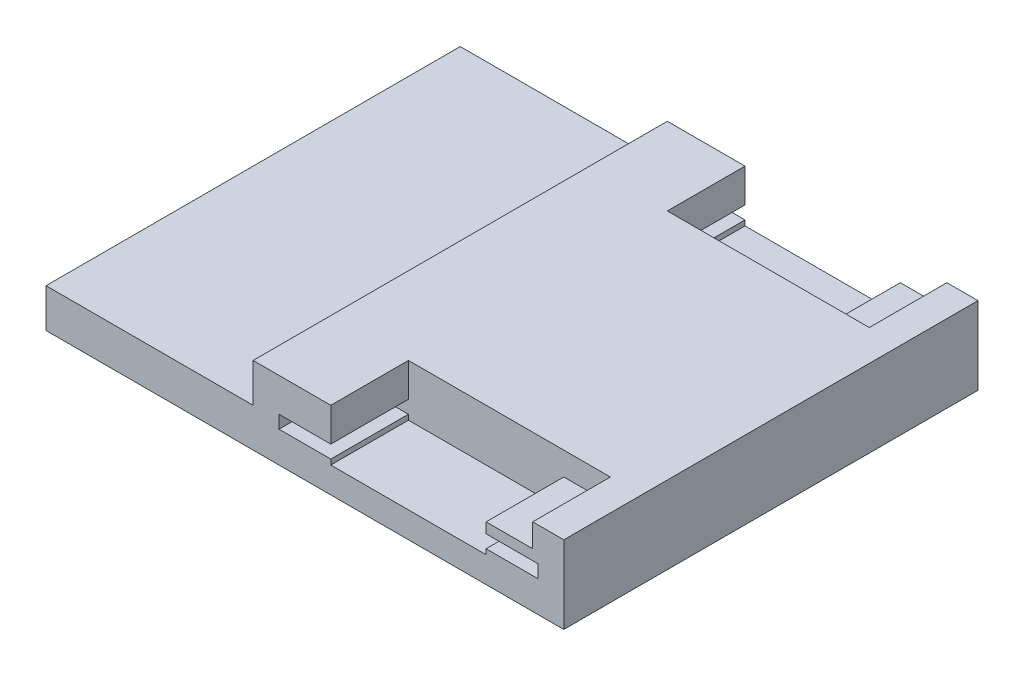
SolidWorks part; units mm, degrees
ref_plane "Front Plane" through (0, 0, 0) normal (0, 0, 1) x (1, 0, 0)
ref_plane "Top Plane" through (0, 0, 0) normal (0, 1, 0) x (1, 0, 0)
ref_plane "Right Plane" through (0, 0, 0) normal (1, 0, 0) x (0, 0, -1)
sketch "Sketch1" plane through (0, 0, 0) normal (0, 1, 0) x (1, 0, 0)
  line L1 (-160, 80) -> (160, 80)
  line L2 (-160, 80) -> (-160, -80)
  line L3 (-160, -80) -> (160, -80)
  line L4 (160, 80) -> (160, -80)
  line L5 (-160, 80) -> (160, -80) construction
  line L6 (-160, -80) -> (160, 80) construction
  point P0 (0, 0)
  dimension "D1" = 320
  dimension "D2" = 160
extrude "Boss-Extrude1" add sketch "Sketch1" along normal blind 20
sketch "Sketch2" plane through (0, 20, 0) normal (0, 1, 0) x (1, 0, 0)
  line L0 (-160, -80) -> (160, -80) construction
  line L1 (-130, -80) -> (-70, -80)
  line L2 (-130, -80) -> (-130, -50)
  line L3 (-130, -50) -> (-70, -50)
  line L4 (-70, -80) -> (-70, -50)
  line L5 (-160, 80) -> (-160, -80) construction
  dimension "D1" = 60
  dimension "D2" = 30
  dimension "D3" = 30
extrude "Cut-Extrude1" cut sketch "Sketch2" against normal blind 28
sketch "Sketch3" plane through (0, 0, 80) normal (0, 0, 1) x (1, 0, 0)
  line L0 (-130, 0) -> (-130, 20) construction
  line L1 (-130, 7) -> (-150, 7)
  line L2 (-130, 7) -> (-130, 2)
  line L3 (-130, 2) -> (-150, 2)
  line L4 (-150, 7) -> (-150, 2)
  line L5 (-160, 0) -> (-130, 0) construction
  line L6 (-70, 0) -> (-70, 20) construction
  line L7 (-70, 7) -> (-50, 7)
  line L8 (-70, 7) -> (-70, 2)
  line L9 (-70, 2) -> (-50, 2)
  line L10 (-50, 7) -> (-50, 2)
  line L11 (88, 0) -> (-88, 0) construction
  dimension "D1" = 2
  dimension "D2" = 5
  dimension "D3" = 20
  dimension "D4" = 20
  dimension "D5" = 5
  dimension "D6" = 2
extrude "Cut-Extrude3" cut sketch "Sketch3" against normal blind 30
mirror "Mirror2" about plane through (0, 0, 0) normal (1, 0, 0) of "Cut-Extrude1", "Cut-Extrude3"
mirror "Mirror3" about plane through (0, 0, 0) normal (0, 0, 1) of "Mirror2", "Cut-Extrude1", "Cut-Extrude3"
sketch "Sketch8" plane through (0, 0, -80) normal (0, 0, -1) x (-1, 0, 0)
  line L0 (-130, 7) -> (-130, 20) construction
  line L1 (-130, 11) -> (-148, 11)
  line L2 (-130, 11) -> (-130, 20)
  line L3 (-130, 20) -> (-148, 20)
  line L4 (-148, 11) -> (-148, 20)
  line L5 (-160, 20) -> (-130, 20) construction
  line L6 (-130, 7) -> (-150, 7) construction
  dimension "D1" = 18
  dimension "D2" = 4
extrude "Cut-Extrude6" cut sketch "Sketch8" against normal blind 30
sketch "Sketch9" plane through (0, 0, -80) normal (0, 0, -1) x (-1, 0, 0)
  line L0 (70, 20) -> (70, 7) construction
  line L1 (70, 11) -> (52, 11)
  line L2 (70, 11) -> (70, 20)
  line L3 (70, 20) -> (52, 20)
  line L4 (52, 11) -> (52, 20)
  line L5 (-70, 20) -> (70, 20) construction
  line L6 (50, 7) -> (70, 7) construction
  dimension "D1" = 18
  dimension "D2" = 4
extrude "Cut-Extrude7" cut sketch "Sketch9" against normal blind 30
sketch "Sketch10" plane through (0, 0, 0) normal (0, -1, 0) x (1, 0, 0)
  line L1 (-160, 80) -> (160, 80)
  line L2 (-160, 80) -> (-160, -80)
  line L3 (-160, -80) -> (160, -80)
  line L4 (160, 80) -> (160, -80)
extrude "Boss-Extrude2" add sketch "Sketch10" along normal blind 10
mirror "Mirror4" about plane through (0, 0, 0) normal (0, 0, 1) of "Cut-Extrude7", "Cut-Extrude6"
sketch "Sketch12" plane through (0, 0, -80) normal (0, 0, -1) x (-1, 0, 0)
  line L0 (-40, 20) -> (-40, 5)
  line L1 (-70, 20) -> (52, 20) construction
  line L2 (-40, 5) -> (40, 5)
  line L3 (40, 5) -> (40, -10)
  line L4 (160, -10) -> (-160, -10) construction
  line L7 (0, 16.5) -> (0, -16.5) construction
  line L8 (-40, 20) -> (160, 20)
  line L9 (160, 20) -> (160, -10)
  line L10 (160, -10) -> (40, -10)
  dimension "D1" = 15
  dimension "D2" = 40
  dimension "D3" = 40
extrude "Cut-Extrude8" cut sketch "Sketch12" against normal blind 236
